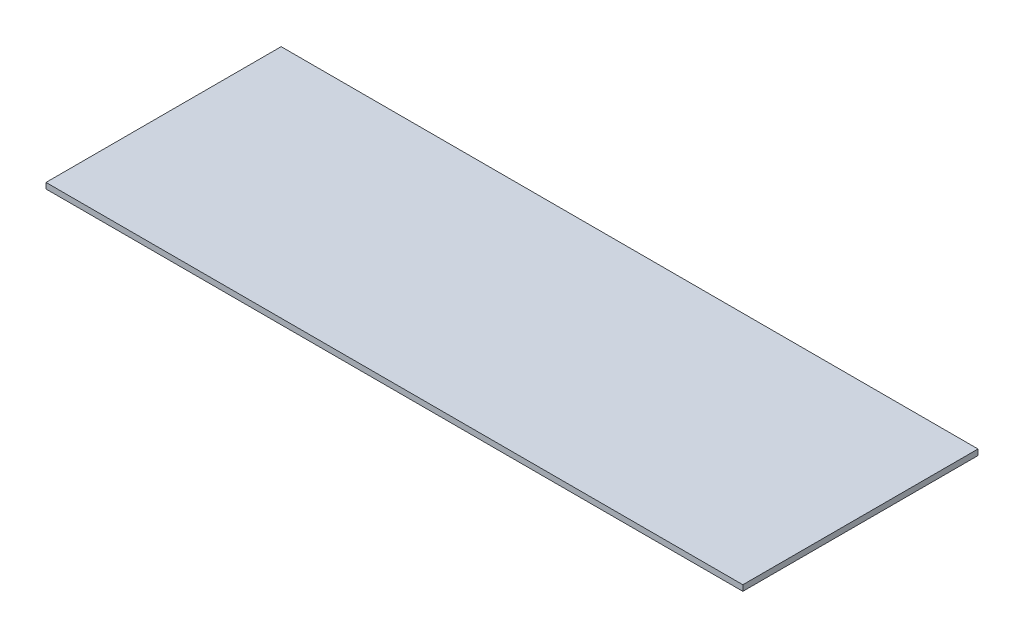
SolidWorks part; units mm, degrees
ref_plane "前视基准面" through (0, 0, 0) normal (0, 0, 1) x (1, 0, 0)
ref_plane "上视基准面" through (0, 0, 0) normal (0, 1, 0) x (1, 0, 0)
ref_plane "右视基准面" through (0, 0, 0) normal (1, 0, 0) x (0, 0, -1)
other "Configuration Table"
sketch "草图1" plane through (0, 0, 0) normal (0, 1, 0) x (1, 0, 0)
  line L1 (-3037.5, -1025) -> (3037.5, -1025)
  line L2 (-3037.5, -1025) -> (-3037.5, 1025)
  line L3 (-3037.5, 1025) -> (3037.5, 1025)
  line L4 (3037.5, -1025) -> (3037.5, 1025)
  line L5 (-3037.5, -1025) -> (3037.5, 1025) construction
  line L6 (-3037.5, 1025) -> (3037.5, -1025) construction
  point P0 (0, 0)
  dimension "D1" = 6075
  dimension "D2" = 2050
extrude "凸台-拉伸1" add sketch "草图1" along normal blind 50
